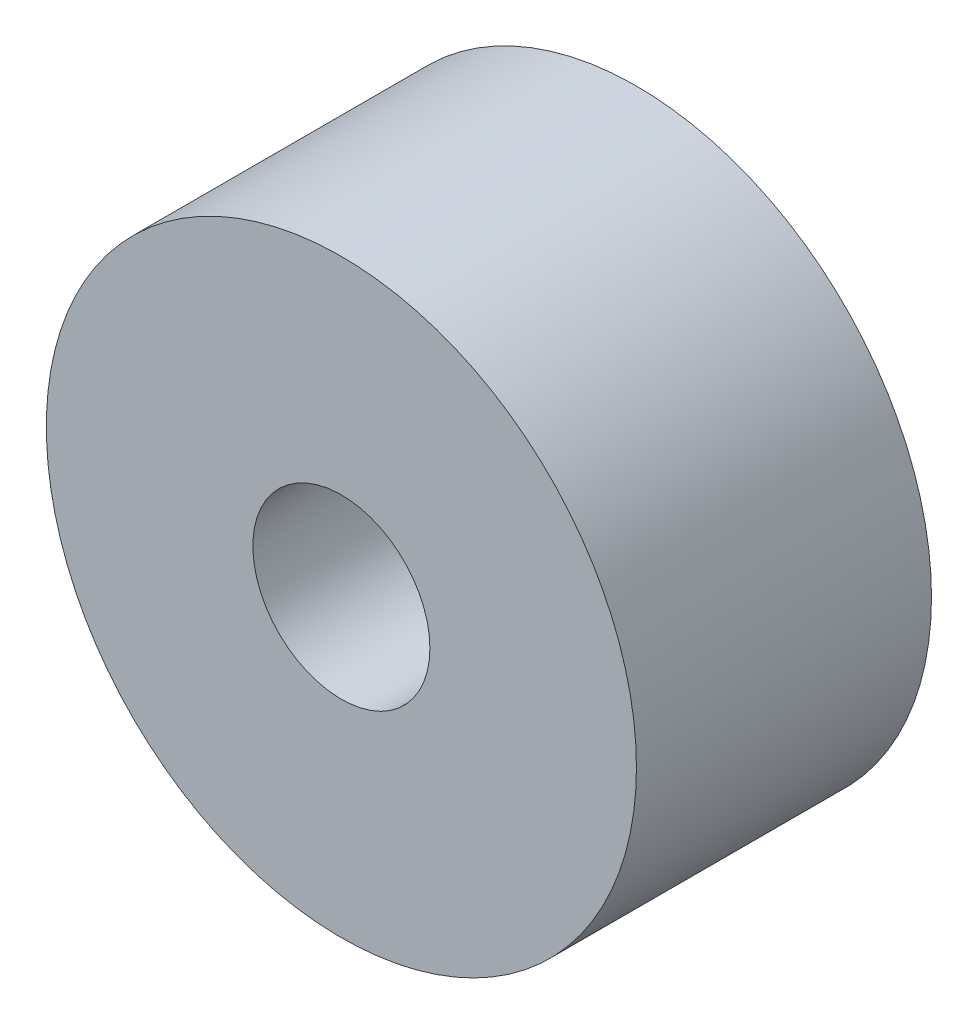
SolidWorks part; units mm, degrees
ref_plane "前视基准面" through (0, 0, 0) normal (0, 0, 1) x (1, 0, 0)
ref_plane "上视基准面" through (0, 0, 0) normal (0, 1, 0) x (1, 0, 0)
ref_plane "右视基准面" through (0, 0, 0) normal (1, 0, 0) x (0, 0, -1)
other "Configuration Table"
sketch "草图1" plane through (0, 0, 0) normal (0, 0, 1) x (1, 0, 0)
  circle A0 centre (0, 0) radius 2.5
  circle A1 centre (0, 0) radius 0.75
extrude "凸台-拉伸1" add sketch "草图1" along normal blind 2.5
